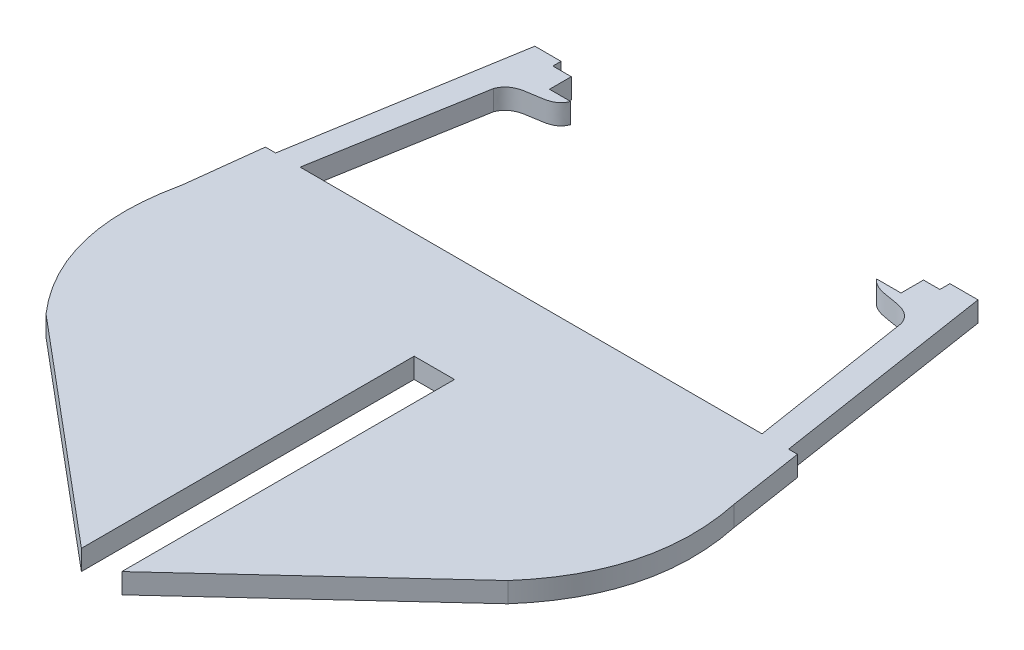
SolidWorks part; units mm, degrees
ref_plane "前视基准面" through (0, 0, 0) normal (0, 0, 1) x (1, 0, 0)
ref_plane "上视基准面" through (0, 0, 0) normal (0, 1, 0) x (1, 0, 0)
ref_plane "右视基准面" through (0, 0, 0) normal (1, 0, 0) x (0, 0, -1)
sketch "草图1" plane through (0, 0, 0) normal (0, 1, 0) x (1, 0, 0)
  line L0 (-68.1139, -204.589) -> (-70.4113, -189.7233)
  line L1 (-70.4113, -189.7233) -> (-72.1682, -189.7233)
  line L2 (-72.1682, -189.7233) -> (-79.0354, -145.2882)
  line L3 (-79.0354, -145.2882) -> (-84.6013, -145.2882)
  line L4 (-84.6013, -145.2882) -> (-84.6013, -147.2885)
  line L5 (-84.6013, -147.2885) -> (-87.8447, -147.2885)
  line L6 (-87.8447, -147.2885) -> (-87.8447, -151.7482)
  line L7 (-87.8447, -151.7482) -> (-92.7099, -151.7482)
  line L8 (-82.5742, -157.0188) -> (-77.4387, -189.7233)
  line L9 (-77.4387, -189.7233) -> (-169.0656, -189.7233)
  line L10 (-169.0656, -189.7233) -> (-163.3896, -157.0188)
  line L11 (-153.5242, -151.613) -> (-157.7136, -151.613)
  line L12 (-157.7136, -151.613) -> (-157.7136, -147.2885)
  line L13 (-157.7136, -147.2885) -> (-161.3624, -147.2885)
  line L14 (-161.3624, -147.2885) -> (-161.3624, -145.6668)
  line L15 (-161.3624, -145.6668) -> (-166.5612, -145.6668)
  line L16 (-166.5612, -145.6668) -> (-173.9307, -189.7233)
  line L17 (-173.9307, -189.7233) -> (-175.9579, -189.7233)
  line L18 (-175.9579, -189.7233) -> (-177.7147, -204.589)
  line L19 (-169.0656, -240.1316) -> (-125.2793, -276.8905)
  line L20 (-125.2793, -276.8905) -> (-125.2793, -210.8905)
  line L21 (-125.2793, -210.8905) -> (-117.2793, -210.8905)
  line L22 (-117.2793, -210.8905) -> (-117.2793, -276.8905)
  line L23 (-117.2793, -276.8905) -> (-77.4387, -240.1316)
  spline S0 degree 3 poles (-92.7099, -151.7482) (-90.0107, -155.0092) (-84.1381, -152.326) (-82.5742, -157.0188) knots 0 0 0 0 1 1 1 1
  spline S1 degree 3 poles (-153.5242, -151.613) (-155.1047, -155.722) (-161.603, -152.4811) (-163.3896, -157.0188) knots 0 0 0 0 1 1 1 1
  spline S2 degree 2 poles (-68.1139, -204.589) (-63.8673, -224.7293) (-77.4387, -240.1316) knots 0 0 0 1 1 1
  spline S3 degree 2 poles (-177.7147, -204.589) (-182.219, -224.9839) (-169.0656, -240.1316) knots 0 0 0 1 1 1
  dimension "D1" = 8
  dimension "D2" = 66
extrude "凸台-拉伸1" add sketch "草图1" along normal blind 4
